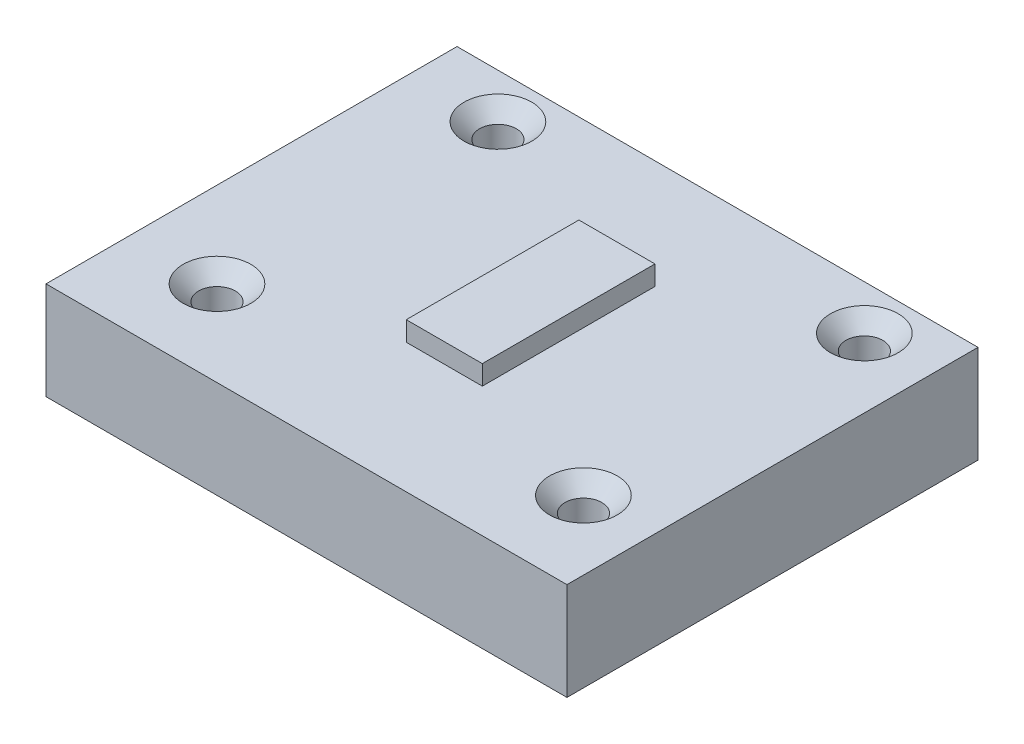
SolidWorks part; units mm, degrees
ref_plane "Front Plane" through (0, 0, 0) normal (0, 0, 1) x (1, 0, 0)
ref_plane "Top Plane" through (0, 0, 0) normal (0, 1, 0) x (1, 0, 0)
ref_plane "Right Plane" through (0, 0, 0) normal (1, 0, 0) x (0, 0, -1)
sketch "Sketch1" plane through (0, 0, 0) normal (0, 1, 0) x (1, 0, 0)
  line L1 (0, 0) -> (203.2, 0)
  line L2 (0, 0) -> (0, 107.1562)
  line L3 (0, 107.1562) -> (203.2, 107.1562)
  line L4 (203.2, 0) -> (203.2, 107.1562)
  dimension "D1" = 203.2
  dimension "D2" = 107.1562
extrude "Boss-Extrude1" add sketch "Sketch1" along normal blind 6.35
hole_wizard "CSK for M2 Flat Head Machine Screw1" positions "Sketch2" profile "Sketch3" countersink size "M2" standard "ANSI Metric" end condition through all
sketch "Sketch2" plane through (0, 6.35, 0) normal (0, 1, 0) x (1, 0, 0)
  line L0 (0, 101.6) -> (203.2, 101.6)
  line L1 (0, 107.1562) -> (0, 0) construction
  line L2 (203.2, 0) -> (203.2, 107.1562) construction
  line L5 (5.5562, 0) -> (5.5563, 107.1562)
  line L6 (0, 0) -> (203.2, 0) construction
  line L7 (203.2, 107.1562) -> (0, 107.1562) construction
  line L10 (29.3687, 107.1562) -> (29.3688, 0)
  line L13 (0, 5.5562) -> (203.2, 5.5562)
  line L16 (197.6437, 0) -> (197.6437, 107.1562)
  line L19 (173.8312, 0) -> (173.8312, 107.1562)
  line L21 (0, 83.3438) -> (203.2, 83.3438)
  line L24 (0, 23.8125) -> (203.2, 23.8125)
  point P0 (5.5562, 101.6)
  point P40 (1.2015, 116.4001)
  point P42 (1.2015, 113.37)
  point P45 (29.3687, 101.6)
  point P47 (5.5563, 5.5562)
  point P49 (29.3688, 5.5562)
  point P51 (173.8312, 5.5562)
  point P53 (173.8312, 101.6)
  point P55 (197.6437, 101.6)
  point P57 (197.6437, 5.5562)
  point P67 (5.5563, 83.3438)
  point P69 (29.3688, 83.3438)
  point P71 (5.5563, 23.8125)
  point P72 (173.8312, 83.3438)
  point P74 (197.6437, 83.3438)
  point P76 (173.8312, 23.8125)
  point P78 (197.6437, 23.8125)
  point P80 (29.3688, 23.8125)
  dimension "D1" = 5.5562
  dimension "D2" = 23.8125
  dimension "D3" = 5.5562
  dimension "D4" = 5.5562
  dimension "D5" = 23.8125
  dimension "D6" = 5.5562
  dimension "D7" = 18.2562
  dimension "D8" = 18.2562
sketch "Sketch3" plane through (5.5562, 6.35, -101.6) normal (1, 0, 0) x (0, 0, 1)
  line L0 (0, 0) -> (0, 6.35)
  line L1 (0, 6.35) -> (1.2, 6.35)
  line L2 (1.2, 6.35) -> (1.2, 1)
  line L3 (1.2, 1) -> (2.2, 0)
  line L5 (2.2, 0) -> (0, 0)
  line L6 (-1.2, 1) -> (-2.2, 0) construction
  line L11 (0, -6.35) -> (0, 107.95) construction
  dimension "Thru Hole Dia." = 2.4
  dimension "Thru Hole Depth" = 6.35
  dimension "Near C'Sink Dia." = 4.4
  dimension "Near C'Sink Angle" = 90
sketch "Sketch4" plane through (0, 6.35, 0) normal (0, 1, 0) x (1, 0, 0)
  line L1 (14.9914, 19.6382) -> (19.9351, 19.6382)
  line L2 (14.9914, 19.6382) -> (14.9914, 8.42)
  line L3 (14.9914, 8.42) -> (19.9351, 8.42)
  line L4 (19.9351, 19.6382) -> (19.9351, 8.42)
extrude "Boss-Extrude2" add sketch "Sketch4" along normal blind 1.27
sketch "Sketch5" plane through (0, 6.35, 0) normal (0, 1, 0) x (1, 0, 0)
  line L1 (33.8552, 115.1265) -> (215.0182, 115.1265)
  line L2 (33.8552, 115.1265) -> (33.8552, -10.9743)
  line L3 (33.8552, -10.9743) -> (215.0182, -10.9743)
  line L4 (215.0182, 115.1265) -> (215.0182, -10.9743)
  line L5 (33.8552, 26.7116) -> (-7.5952, 26.7116)
  line L6 (33.8552, 26.7116) -> (33.8552, 115.1265)
  line L7 (33.8552, 115.1265) -> (-7.5952, 115.1265)
  line L8 (-7.5952, 26.7116) -> (-7.5952, 115.1265)
  line M9 (0, 107.1562) -> (0, 0)
  line M10 (0, 0) -> (203.2, 0)
  line M11 (203.2, 0) -> (203.2, 107.1562)
  line M12 (203.2, 107.1562) -> (0, 107.1562)
  circle M14 centre (197.6437, 23.8125) radius 2.2
  circle M15 centre (173.8312, 23.8125) radius 2.2
  circle M16 centre (197.6437, 83.3438) radius 2.2
  circle M17 centre (173.8312, 83.3438) radius 2.2
  circle M19 centre (29.3688, 83.3438) radius 2.2
  circle M20 centre (5.5563, 83.3438) radius 2.2
  circle M21 centre (197.6437, 5.5562) radius 2.2
  circle M22 centre (197.6437, 101.6) radius 2.2
  circle M23 centre (173.8312, 101.6) radius 2.2
  circle M24 centre (173.8312, 5.5562) radius 2.2
  circle M27 centre (29.3687, 101.6) radius 2.2
  circle M28 centre (5.5562, 101.6) radius 2.2
extrude "Cut-Extrude1" cut sketch "Sketch5" against normal through all contours L2 M12 M10 M11 M14 M16 M22 M24 M23 M21 M17 M15 | L5 L2 M12 M9 M19 M27 M28 M20 | M20 | M28 | M27 | M19 | M23 | M22 | M17 | M16 | M15 | M14 | M24 | M21
